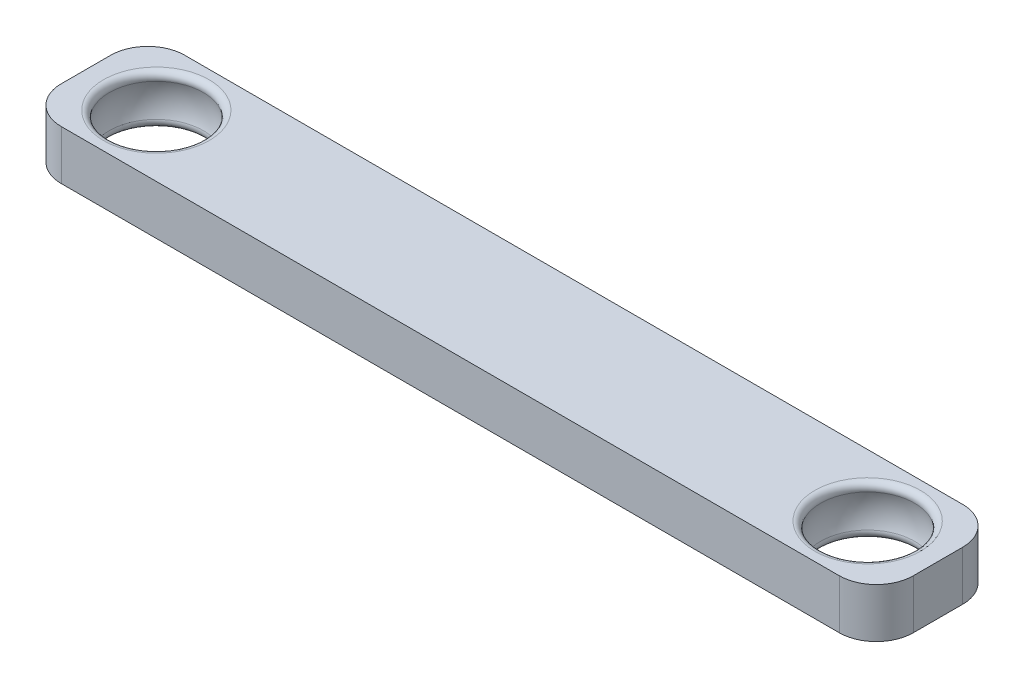
SolidWorks part; units mm, degrees
ref_plane "Front Plane" through (0, 0, 0) normal (0, 0, 1) x (1, 0, 0)
ref_plane "Top Plane" through (0, 0, 0) normal (0, 1, 0) x (1, 0, 0)
ref_plane "Right Plane" through (0, 0, 0) normal (1, 0, 0) x (0, 0, -1)
sketch "Sketch1" plane through (0, 0, 0) normal (0, 1, 0) x (1, 0, 0)
  line L1 (-34.5, 5) -> (34.5, 5)
  line L2 (-34.5, 5) -> (-34.5, -5)
  line L3 (-34.5, -5) -> (34.5, -5)
  line L4 (34.5, 5) -> (34.5, -5)
  line L5 (-34.5, 5) -> (34.5, -5) construction
  line L6 (-34.5, -5) -> (34.5, 5) construction
  point P0 (0, 0)
  dimension "D1" = 10
  dimension "D2" = 69
extrude "Boss-Extrude1" add sketch "Sketch1" along normal blind 4
sketch "Sketch2" plane through (0, 0, 0) normal (0, 0, 1) x (1, 0, 0)
  line L0 (-28.8, 4) -> (-28.8, 0)
  line L1 (-34.5, 4) -> (34.5, 4) construction
  line L2 (-34.5, 0) -> (34.5, 0) construction
  line L3 (-28.8, 4) -> (-32.3, 4)
  line L4 (-28.8, 0) -> (-32.3, 0)
  arc A0 (-32.3, 4) -> (-32.3, 0) centre (-28.8, 2) ccw
  dimension "D1" = 28.8
  dimension "D2" = 3.5
revolve "Cut-Revolve2" cut sketch "Sketch2" angle 360 about L0
fillet "Fillet1" radius 3 4 edges at (34.5, 2, -5) (34.5, 2, 5) (-34.5, 2, -5) (-34.5, 2, 5)
mirror "Mirror1" about plane through (0, 0, 0) normal (1, 0, 0) of "Cut-Revolve2"
fillet "Fillet2" radius 0.5 4 edges at (-28.8, 0, 3.5) (28.8, 0, 3.5) (28.8, 4, 3.5) (-28.8, 4, 3.5)
